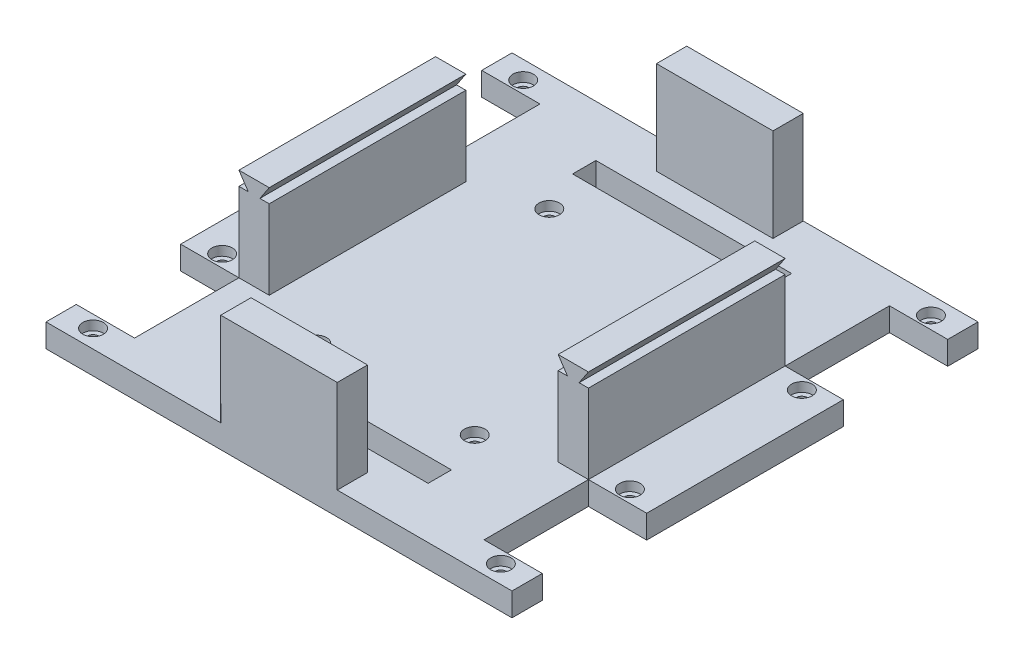
SolidWorks part; units mm, degrees
ref_plane "Front" through (0, 0, 0) normal (0, 0, 1) x (1, 0, 0)
ref_plane "Top" through (0, 0, 0) normal (0, 1, 0) x (1, 0, 0)
ref_plane "Right" through (0, 0, 0) normal (1, 0, 0) x (0, 0, -1)
sketch "草图1" plane through (0, 0, 0) normal (0, 1, 0) x (1, 0, 0)
  line L1 (-50, 50) -> (50, 50)
  line L2 (-50, 50) -> (-50, -50)
  line L3 (-50, -50) -> (50, -50)
  line L4 (50, 50) -> (50, -50)
  line L5 (-50, 50) -> (50, -50) construction
  line L6 (-50, -50) -> (50, 50) construction
  point P0 (0, 0)
  dimension "D1" = 100
  dimension "D2" = 100
extrude "凸台-拉伸1" add sketch "草图1" along normal blind 5
sketch "草图2" plane through (0, 5, 0) normal (0, 1, 0) x (1, 0, 0)
  line L0 (-37.5, 43.5) -> (-37.5, 21.1)
  line L1 (50, 50) -> (-50, 50) construction
  line L3 (37.5, 43.5) -> (37.5, 21.1)
  line L4 (-50, 50) -> (-50, -50) construction
  line L5 (50, -50) -> (50, 50) construction
  line L6 (-37.5, 43.5) -> (-50, 43.5)
  line L7 (37.5, 43.5) -> (50, 43.5)
  line L8 (-50, 21.1) -> (-37.5, 21.1)
  line L9 (-50, 43.5) -> (-50, 21.1)
  line L10 (37.5, 21.1) -> (50, 21.1)
  line L11 (50, 21.1) -> (50, 43.5)
  line L12 (-50, 0) -> (50, 0) construction
  line L13 (37.5, -21.1) -> (50, -21.1)
  line L14 (50, -21.1) -> (50, -43.5)
  line L15 (37.5, -43.5) -> (50, -43.5)
  line L16 (-37.5, -43.5) -> (-50, -43.5)
  line L17 (-50, -43.5) -> (-50, -21.1)
  line L18 (-50, -21.1) -> (-37.5, -21.1)
  line L19 (-37.5, -21.1) -> (-37.5, -43.5)
  line L20 (37.5, -21.1) -> (37.5, -43.5)
  dimension "D1" = 12.5
  dimension "D2" = 12.5
  dimension "D3" = 6.5
  dimension "D4" = 22.4
extrude "切除-拉伸1" cut sketch "草图2" against normal up to next
sketch "草图3" plane through (0, 5, 0) normal (0, 1, 0) x (1, 0, 0)
  line L0 (-37.5, 32.3) -> (-50, 32.3) construction
  line L1 (-37.5, 21.1) -> (-37.5, 43.5) construction
  line L8 (-43.75, 50) -> (-43.75, 32.3) construction
  line L9 (50, 50) -> (-50, 50) construction
  line L10 (-50, 0) -> (50, 0) construction
  line L11 (-50, 21.1) -> (-50, -21.1) construction
  line L12 (50, -21.1) -> (50, 21.1) construction
  line L13 (0, 50) -> (0, -51.3373) construction
  circle A0 centre (-43.75, 46.15) radius 1.2
  circle A1 centre (-43.75, 18.45) radius 1.2
  circle A2 centre (43.75, 46.15) radius 1.2
  circle A3 centre (43.75, 18.45) radius 1.2
  circle A4 centre (43.75, -18.45) radius 1.2
  circle A5 centre (43.75, -46.15) radius 1.2
  circle A6 centre (-43.75, -18.45) radius 1.2
  circle A7 centre (-43.75, -46.15) radius 1.2
  dimension "D1" = 27.7
hole_wizard "M2 凹头盖螺钉的柱形沉头孔3" positions "3D草图3" profile "草图6" counterbore size "M2" standard "ANSI Metric" end condition up to next
sketch3d "3D草图3"
  point P0 (-43.75, 5, -46.15)
  point P3 (43.75, 5, -46.15)
  point P6 (43.75, 5, -18.45)
  point P9 (-43.75, 5, -18.45)
  point P12 (-43.75, 5, 18.45)
  point P15 (-43.75, 5, 46.15)
  point P18 (43.75, 5, 18.45)
  point P21 (43.75, 5, 46.15)
sketch "草图6" plane through (-43.75, 5, -46.15) normal (1, 0, 0) x (0, 0, 1)
  line L0 (0, 0) -> (0, 5)
  line L1 (0, 5) -> (1.2, 5)
  line L3 (1.2, 5) -> (1.2, 2)
  line L4 (1.2, 2) -> (2.2, 2)
  line L5 (2.2, 2) -> (2.2, 0)
  line L7 (2.2, 0) -> (0, 0)
  line L11 (0, -6.35) -> (0, 107.95) construction
  dimension "通孔孔直径" = 2.4
  dimension "通孔孔深度" = 5
  dimension "柱形沉头孔直径" = 4.4
  dimension "柱形沉头孔深度" = 2
sketch "草图9" plane through (0, 5, 0) normal (0, 1, 0) x (1, 0, 0)
  line L0 (0, 50) -> (0, -51.3373) construction
  line L2 (-12.5, 43.5) -> (12.5, 43.5)
  line L3 (-12.5, 43.5) -> (-12.5, 50)
  line L4 (-12.5, 50) -> (12.5, 50)
  line L5 (12.5, 43.5) -> (12.5, 50)
  line L7 (-12.5, 43.5) -> (12.5, 50) construction
  line L8 (-12.5, 50) -> (12.5, 43.5) construction
  line L9 (50, 50) -> (-50, 50) construction
  line L10 (-50, -50) -> (50, -50) construction
  line L11 (-12.5, -43.5) -> (12.5, -43.5)
  line L12 (-12.5, -43.5) -> (-12.5, -50)
  line L13 (-12.5, -50) -> (12.5, -50)
  line L14 (12.5, -43.5) -> (12.5, -50)
  line L15 (-12.5, -43.5) -> (12.5, -50) construction
  line L16 (-12.5, -50) -> (12.5, -43.5) construction
  line L18 (-37.5, 21.1) -> (-31, 21.1)
  line L19 (-37.5, 21.1) -> (-37.5, -21.1)
  line L20 (-37.5, -21.1) -> (-31, -21.1)
  line L21 (-31, 21.1) -> (-31, -21.1)
  line L22 (37.5, 21.1) -> (31, 21.1)
  line L23 (37.5, 21.1) -> (37.5, -21.1)
  line L24 (37.5, -21.1) -> (31, -21.1)
  line L25 (31, 21.1) -> (31, -21.1)
  point P0 (0, 46.75)
  point P9 (0, -46.75)
  dimension "D2" = 25
  dimension "D3" = 6.5
  dimension "D4" = 6.5
  dimension "D1" = 6.5
  dimension "D5" = 6.5
extrude "凸台-拉伸4" add sketch "草图9" along normal blind 20
sketch "草图10" plane through (0, 5, 0) normal (0, 1, 0) x (1, 0, 0)
  line L1 (-21, -29) -> (21, -29) construction
  line L2 (-21, -29) -> (-21, 29) construction
  line L3 (-21, 29) -> (21, 29) construction
  line L4 (21, -29) -> (21, 29) construction
  line L5 (-21, -29) -> (21, 29) construction
  line L6 (-21, 29) -> (21, -29) construction
  point P0 (0, 0)
  point P6 (-17, 25)
  point P7 (17, 25)
  point P8 (-17, -25)
  point P9 (17, -25)
  dimension "D3" = 4
  dimension "D1" = 58
  dimension "D2" = 42
  dimension "D4" = 4
  dimension "D5" = 4
  dimension "D6" = 4
  dimension "D7" = 4
  dimension "D8" = 4
  dimension "D9" = 4
  dimension "D10" = 4
hole_wizard "M2 凹头盖螺钉的柱形沉头孔4" positions "3D草图4" profile "草图11" counterbore size "M2" standard "ANSI Metric" end condition up to next
sketch3d "3D草图4"
  point P0 (-17, 5, -25)
  point P3 (17, 5, -25)
  point P6 (-17, 5, 25)
  point P9 (17, 5, 25)
sketch "草图11" plane through (-17, 5, -25) normal (1, 0, 0) x (0, 0, 1)
  line L0 (0, 0) -> (0, 5)
  line L1 (0, 5) -> (1.2, 5)
  line L3 (1.2, 5) -> (1.2, 2)
  line L4 (1.2, 2) -> (2.2, 2)
  line L5 (2.2, 2) -> (2.2, 0)
  line L7 (2.2, 0) -> (0, 0)
  line L11 (0, -6.35) -> (0, 107.95) construction
  dimension "通孔孔直径" = 2.4
  dimension "通孔孔深度" = 5
  dimension "柱形沉头孔直径" = 4.4
  dimension "柱形沉头孔深度" = 2
sketch "草图12" plane through (0, 5, 0) normal (0, 1, 0) x (1, 0, 0)
  line L0 (0, 50) -> (0, -51.3373) construction
  line L1 (21, 39) -> (-21, 39)
  line L2 (21, 39) -> (21, 34)
  line L3 (21, 34) -> (-21, 34)
  line L4 (-21, 39) -> (-21, 34)
  line L5 (21, 39) -> (-21, 34) construction
  line L6 (21, 34) -> (-21, 39) construction
  line L7 (-21, 29) -> (21, 29) construction
  line L8 (-50, 0) -> (50, 0) construction
  line L9 (21, -39) -> (21, -34)
  line L10 (21, -34) -> (-21, -34)
  line L11 (-21, -39) -> (-21, -34)
  line L12 (21, -39) -> (-21, -39)
  point P0 (0, 36.5)
  dimension "D1" = 5
  dimension "D2" = 5
extrude "切除-拉伸2" cut sketch "草图12" against normal blind 10
sketch "草图15" plane through (0, 0, 21.1) normal (0, 0, 1) x (1, 0, 0)
  line L0 (-37.5, 25) -> (-37.5, 22)
  line L1 (-37.5, 25) -> (-37.5, 5) construction
  line L3 (-37.5, 22) -> (-35.5, 22)
  line L4 (-37.5, 25) -> (-35.5, 22)
  line L5 (-34.25, 25) -> (-34.25, 5) construction
  line L7 (-37.5, 25) -> (-31, 25) construction
  line L8 (-50, 5) -> (50, 5) construction
  line L9 (-31, 25) -> (-31, 22)
  line L10 (-31, 22) -> (-33, 22)
  line L11 (-31, 25) -> (-33, 22)
  line L12 (0, 25) -> (0, 0) construction
  line L13 (-12.5, 25) -> (12.5, 25) construction
  line L14 (37.5, 25) -> (37.5, 22)
  line L15 (31, 22) -> (33, 22)
  line L16 (31, 25) -> (33, 22)
  line L17 (37.5, 22) -> (35.5, 22)
  line L18 (37.5, 25) -> (35.5, 22)
  line L19 (31, 25) -> (31, 22)
  dimension "D1" = 3
  dimension "D2" = 2
extrude "切除-拉伸3" cut sketch "草图15" against normal through all
